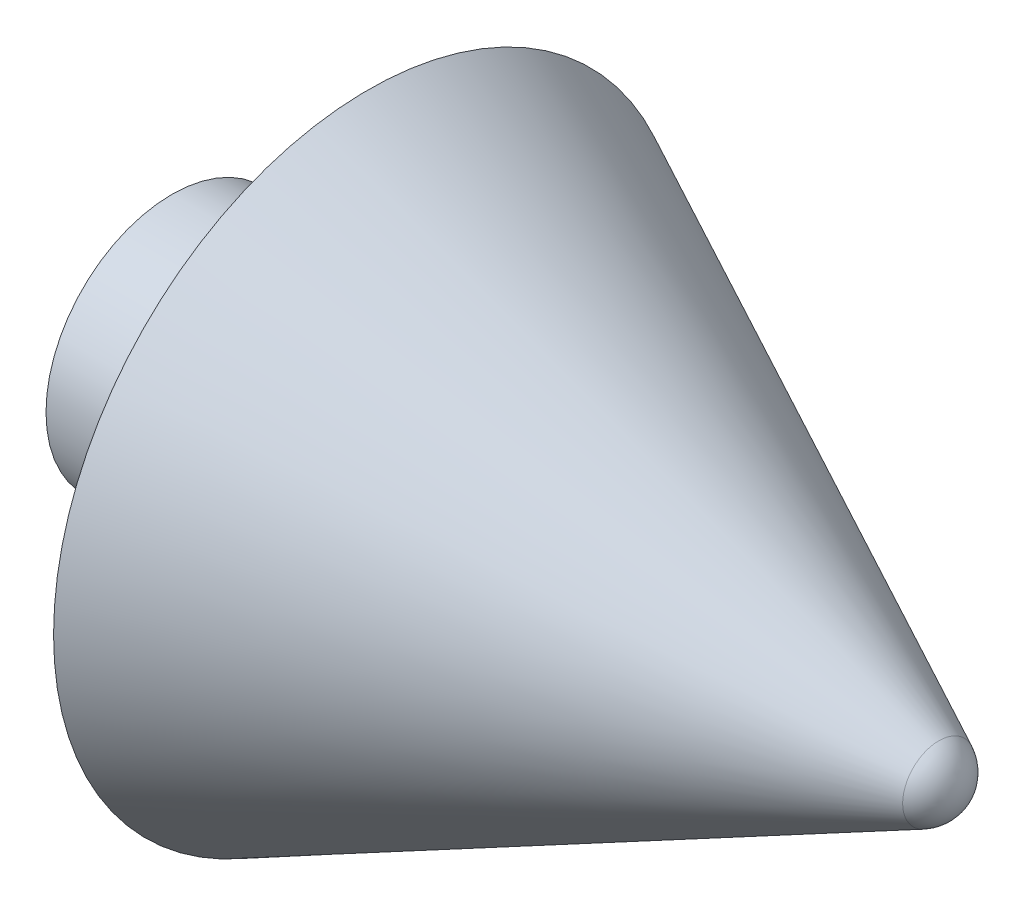
SolidWorks part; units mm, degrees
material "Aluminum Bronze"
ref_plane "Front Plane" through (0, 0, 0) normal (0, 0, 1) x (1, 0, 0)
ref_plane "Top Plane" through (0, 0, 0) normal (0, 1, 0) x (1, 0, 0)
ref_plane "Right Plane" through (0, 0, 0) normal (1, 0, 0) x (0, 0, -1)
sketch "Sketch1" plane through (0, 0, 0) normal (0, 0, 1) x (1, 0, 0)
  line L0 (0, -3.175) -> (0, 3.175)
  line L1 (3.175, 4.7625) -> (4.953, 4.7625)
  line L2 (4.953, 6.2865) -> (4.953, 7.9375)
  line L3 (4.953, 7.9375) -> (19.355, 0.9132)
  line L4 (21.2273, 0) -> (0, 0) construction
  line L5 (4.953, -7.9375) -> (19.355, -0.9132)
  line L6 (4.953, -6.2865) -> (4.953, -7.9375)
  line L7 (3.175, -4.7625) -> (4.953, -4.7625)
  line L8 (3.175, 4.7625) -> (3.175, 3.175)
  line L9 (1.651, 3.175) -> (0, 3.175)
  line L10 (3.175, -4.7625) -> (3.175, -3.175)
  line L11 (3.175, -3.175) -> (0, -3.175)
  arc A0 (19.355, -0.9132) -> (19.355, 0.9132) centre (18.9096, 0) ccw
  arc A1 (4.953, -4.7625) -> (4.953, -6.2865) centre (4.953, -5.5245) cw
  arc A2 (4.953, 4.7625) -> (4.953, 6.2865) centre (4.953, 5.5245) ccw
  arc A3 (3.175, 3.175) -> (1.651, 3.175) centre (2.413, 3.175) cw
  dimension "D1" = 1.016
  dimension "D5" = 0.762
  dimension "D2" = 9.525
  dimension "D3" = 1.778
  dimension "D4" = 3.175
  dimension "D6" = 26
  dimension "D7" = 6.35
  dimension "D8" = 3.175
ref_axis "Axis1" through (-1.4672, 0, 0) along (1, 0, 0)
revolve "Revolve1" add sketch "Sketch1" angle 360 about axis through (-1.4672, 0, 0) along (1, 0, 0)
hole_wizard "#8-32 Tapped Hole1" positions "Sketch2" profile "Sketch3" tap size "#8-32" standard "ANSI Inch"
sketch "Sketch2" plane through (0, 0, 0) normal (-1, 0, 0) x (0, 0, 1)
  point P0 (0, 0)
sketch "Sketch3" plane through (0, 0, 0) normal (0, 1, 0) x (0, 0, 1)
  line L0 (0, 0) -> (0, 12.4678)
  line L1 (0, 12.4678) -> (1.7272, 11.43)
  line L2 (1.7272, 11.43) -> (1.7272, 0)
  line L5 (1.7272, 0) -> (0, 0)
  line L10 (0, 12.4678) -> (-1.7272, 11.43) construction
  line L11 (0, -6.35) -> (0, 107.95) construction
  dimension "Tap Drill Dia." = 3.4544
  dimension "Tap Drill Depth" = 11.43
  dimension "Drill Angle" = 118
cosmetic thread "Hole Thread1" parameters "D1"=8.382, "D2"=4.1656
